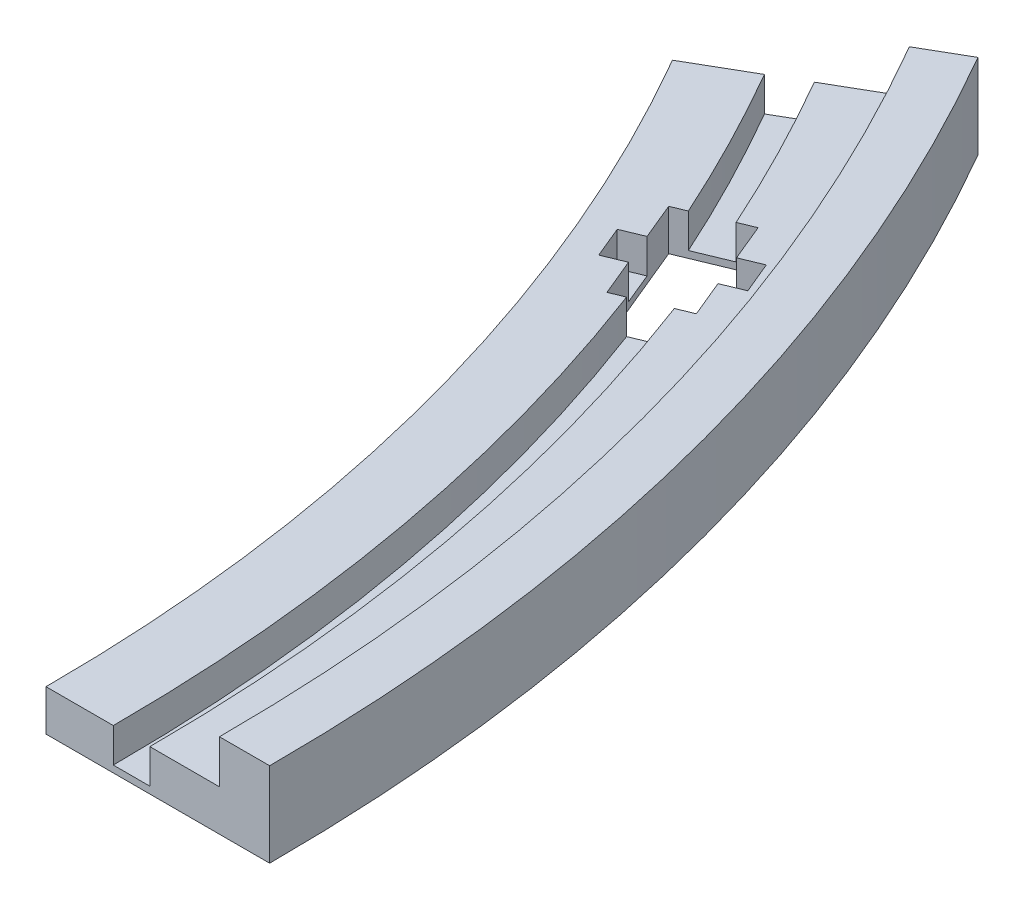
SolidWorks part; units mm, degrees
ref_plane "Ebene vorne" through (0, 0, 0) normal (0, 0, 1) x (1, 0, 0)
ref_plane "Ebene oben" through (0, 0, 0) normal (0, 1, 0) x (1, 0, 0)
ref_plane "Ebene rechts" through (0, 0, 0) normal (1, 0, 0) x (0, 0, -1)
sketch "Skizze1" plane through (0, 0, 0) normal (0, 1, 0) x (1, 0, 0)
  line L0 (0, 0) -> (169.6, 0) construction
  line L1 (146.8779, 84.8) -> (129.9038, 75)
  line L2 (150, 0) -> (169.6, 0)
  line L3 (0, 0) -> (146.8779, 84.8) construction
  arc A0 (150, 0) -> (129.9038, 75) centre (0, 0) ccw
  arc A1 (169.6, 0) -> (146.8779, 84.8) centre (0, 0) ccw
  dimension "D1" = 169.6
  dimension "D2" = 150
  dimension "D5" = 30
extrude "Aufsatz-Linear austragen1" add sketch "Skizze1" along normal blind 3.6
sketch "Skizze2" plane through (0, 3.6, 0) normal (0, 1, 0) x (1, 0, 0)
  line L0 (150, 0) -> (169.6, 0) construction
  line L1 (146.8779, 84.8) -> (129.9038, 75) construction
  line L2 (135.0134, 77.95) -> (137.7846, 79.55)
  line L5 (155.9, 0) -> (159.1, 0)
  arc A0 (155.9, 0) -> (135.0134, 77.95) centre (0, 0) ccw
  arc A1 (159.1, 0) -> (137.7846, 79.55) centre (0, 0) ccw
  dimension "D4" = 5.9
  dimension "D3" = 3.2
extrude "Schnitt-Linear austragen1" cut sketch "Skizze2" against normal blind 3
sketch "Skizze3" plane through (0, 3.6, 0) normal (0, 1, 0) x (1, 0, 0)
  line L0 (159.1, 0) -> (169.6, 0) construction
  line L1 (146.8779, 84.8) -> (137.7846, 79.55) construction
  line L2 (0, 0) -> (145.511, 60.2726) construction
  line L3 (0, 0) -> (150, 0) construction
  line L5 (140.826, 63.744) -> (146.3692, 66.0401)
  line L6 (146.3692, 66.0401) -> (150.1961, 56.8013)
  line L7 (150.1961, 56.8013) -> (144.6528, 54.5052)
  line L8 (144.6528, 54.5052) -> (140.826, 63.744)
  line L9 (144.6528, 54.5052) -> (146.3692, 66.0401) construction
  arc A0 (157.5, 0) -> (136.399, 78.75) centre (0, 0) ccw construction
  point P8 (142.1766, 0)
  point P18 (145.511, 60.2726)
  dimension "D1" = 157.5
  dimension "D3" = 22.5
  dimension "D5" = 10
  dimension "D6" = 6
extrude "Schnitt-Linear austragen2" cut sketch "Skizze3" against normal through all
sketch "Skizze4" plane through (0, 3.6, 0) normal (0, 1, 0) x (1, 0, 0)
  line L0 (140.3176, 59.745) -> (149.5564, 63.5719)
  line L1 (149.5564, 63.5719) -> (150.7044, 60.8002)
  line L2 (150.7044, 60.8002) -> (141.4657, 56.9734)
  line L3 (141.4657, 56.9734) -> (140.3176, 59.745)
  line L8 (142.0453, 64.2491) -> (140.826, 63.744) construction
  line L9 (140.826, 63.744) -> (144.6528, 54.5052) construction
  line L12 (141.4657, 56.9734) -> (149.5564, 63.5719) construction
  line L13 (144.6528, 54.5052) -> (146.3692, 66.0401) construction
  point P20 (145.511, 60.2726)
  point P21 (145.511, 60.2726)
  dimension "D1" = 10
  dimension "D2" = 3
extrude "Schnitt-Linear austragen3" cut sketch "Skizze4" against normal blind 3
sketch "Skizze5" plane through (0, 3.6, 0) normal (0, 1, 0) x (1, 0, 0)
  line L0 (143.0674, 82.6) -> (146.8779, 84.8)
  line L1 (165.2, 0) -> (169.6, 0)
  line L2 (159.1, 0) -> (169.6, 0) construction
  line L3 (146.8779, 84.8) -> (137.7846, 79.55) construction
  arc A0 (169.6, 0) -> (146.8779, 84.8) centre (0, 0) ccw
  arc A1 (165.2, 0) -> (143.0674, 82.6) centre (0, 0) ccw
  dimension "D1" = 4.4
extrude "Aufsatz-Linear austragen2" add sketch "Skizze5" along normal blind 3.8
